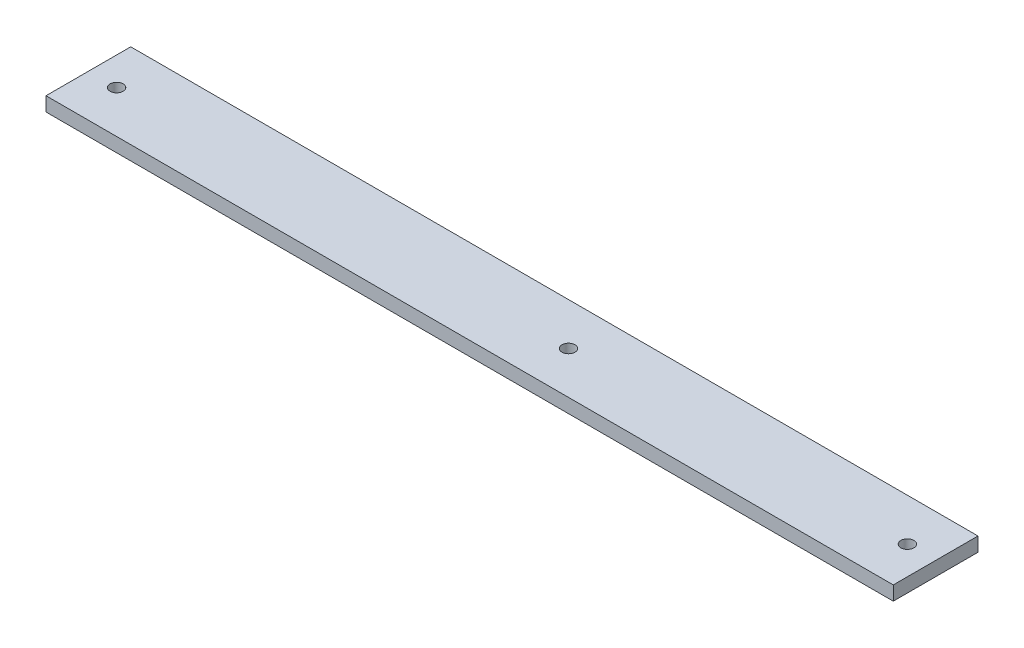
SolidWorks part; units mm, degrees
ref_plane "Front Plane" through (0, 0, 0) normal (0, 0, 1) x (1, 0, 0)
ref_plane "Top Plane" through (0, 0, 0) normal (0, 1, 0) x (1, 0, 0)
ref_plane "Right Plane" through (0, 0, 0) normal (1, 0, 0) x (0, 0, -1)
sketch "Sketch2" plane through (0, 0, 0) normal (0, 1, 0) x (1, 0, 0)
  line L1 (0, 0) -> (190.5, 0)
  line L2 (0, 0) -> (0, 19.05)
  line L3 (0, 19.05) -> (190.5, 19.05)
  line L4 (190.5, 0) -> (190.5, 19.05)
  circle A0 centre (6.35, 9.525) radius 1.4605
  circle A1 centre (184.15, 9.525) radius 1.4605
  circle A2 centre (107.95, 9.525) radius 1.4605
  dimension "D3" = 2.921
  dimension "D5" = 2.921
  dimension "D7" = 2.921
  dimension "D9" = 9.525
  dimension "D1" = 19.05
  dimension "D2" = 190.5
  dimension "D4" = 6.35
  dimension "D6" = 6.35
  dimension "D8" = 107.95
  dimension "D10" = 9.525
  dimension "D11" = 9.525
extrude "Boss-Extrude1" add sketch "Sketch2" along normal blind 3.175
